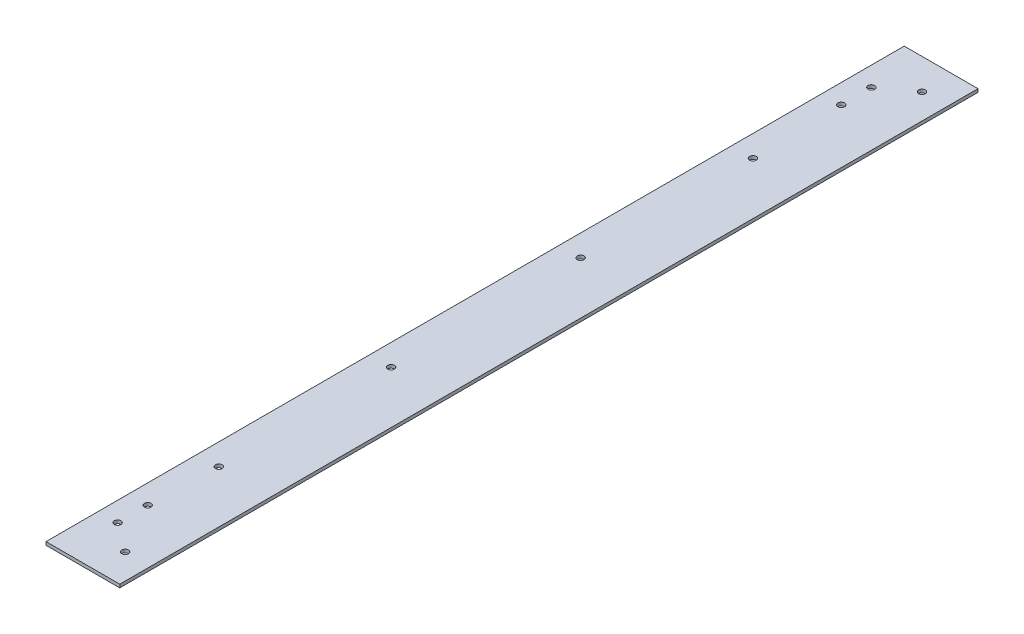
SolidWorks part; units mm, degrees
ref_plane "Alzado" through (0, 0, 0) normal (0, 0, 1) x (1, 0, 0)
ref_plane "Planta" through (0, 0, 0) normal (0, 1, 0) x (1, 0, 0)
ref_plane "Vista lateral" through (0, 0, 0) normal (1, 0, 0) x (0, 0, -1)
sketch "Croquis1" plane through (0, 0, 0) normal (0, 1, 0) x (1, 0, 0)
  line L1 (0, 0) -> (35, 0)
  line L2 (0, 0) -> (0, -400)
  line L3 (0, -400) -> (35, -400)
  line L4 (35, 0) -> (35, -400)
  dimension "D1" = 35
  dimension "D2" = 400
extrude "Saliente-Extruir1" add sketch "Croquis1" along normal blind 1.5
sketch "Croquis2" plane through (0, 1.5, 0) normal (0, 1, 0) x (1, 0, 0)
  line L0 (35, 0) -> (0, 0) construction
  line L1 (35, -400) -> (35, 0) construction
  line L2 (0, -400) -> (35, -400) construction
  circle A0 centre (22.5, -15) radius 1.55
  circle A1 centre (22.5, -385) radius 1.55
  dimension "D1" = 3.1
  dimension "D2" = 15
  dimension "D4" = 3.1
  dimension "D3" = 12.5
  dimension "D5" = 15
  dimension "D6" = 12.5
extrude "Cortar-Extruir1" cut sketch "Croquis2" against normal up to surface (1.5 mm away) up to face at (17.5, 0, 200)
sketch "Croquis3" plane through (0, 1.5, 0) normal (0, 1, 0) x (1, 0, 0)
  line L0 (0, 0) -> (0, -400) construction
  line L1 (35, 0) -> (0, 0) construction
  line L2 (0, -400) -> (35, -400) construction
  line L3 (0, 0) -> (0, -400) construction
  line L4 (35, -200) -> (0, -200) construction
  line L5 (35, -400) -> (35, 0) construction
  line L6 (35, 0) -> (0, 0) construction
  circle A0 centre (9, -25) radius 1.55
  circle A1 centre (9, -39) radius 1.55
  circle A2 centre (9, -375) radius 1.55
  circle A3 centre (9, -361) radius 1.55
  dimension "D1" = 3.1
  dimension "D5" = 3.1
  dimension "D2" = 14
  dimension "D3" = 9
  dimension "D4" = 25
  dimension "D6" = 14
  dimension "D7" = 25
  dimension "D8" = 9
  dimension "D9" = 200
extrude "Cortar-Extruir2" cut sketch "Croquis3" against normal up to surface (1.5 mm away) up to face at (22.5, 0, 16.55)
sketch "Croquis5" plane through (0, 1.5, 0) normal (0, 1, 0) x (1, 0, 0)
  line L0 (0, -400) -> (35, -400) construction
  line L1 (35, -400) -> (35, 0) construction
  line L2 (35, 0) -> (0, 0) construction
  circle A0 centre (10, -81) radius 1.55
  circle A1 centre (10, -161) radius 1.55
  circle A2 centre (10, -249) radius 1.55
  circle A3 centre (10, -329) radius 1.55
  dimension "D1" = 3.1
  dimension "D7" = 71
  dimension "D2" = 80
  dimension "D3" = 80
  dimension "D4" = 25
  dimension "D5" = 25
  dimension "D6" = 81
extrude "Cortar-Extruir3" cut sketch "Croquis5" against normal up to surface (1.5 mm away) up to face at (9, 0, 26.55)
sketch "Croquis6" plane through (0, 1.5, 0) normal (0, 1, 0) x (1, 0, 0)
  line L8 (0.75, -0.75) -> (0.75, -399.25)
  line L9 (0.75, -399.25) -> (34.25, -399.25)
  line L10 (34.25, -399.25) -> (34.25, -0.75)
  line L11 (34.25, -0.75) -> (0.75, -0.75)
  line L12 (0.75, -0.75) -> (0.75, -399.25)
  line L13 (0.75, -399.25) -> (34.25, -399.25)
  line L14 (34.25, -399.25) -> (34.25, -0.75)
  line L15 (34.25, -0.75) -> (0.75, -0.75)
  dimension "D1" = 0.75
extrude "Cortar-Extruir4" cut sketch "Croquis6" against normal up to surface (1.5 mm away) flip side to cut up to face at (10, 0, 82.55)
sketch "Croquis7" plane through (0, 1.5, 0) normal (0, 1, 0) x (1, 0, 0)
  line L1 (0.75, -0.75) -> (0, -0.75)
  line L2 (0.75, -0.75) -> (0.75, -399.25)
  line L3 (0.75, -399.25) -> (0, -399.25)
  line L4 (0, -0.75) -> (0, -399.25)
  point P5 (0.75, -399.25)
  dimension "D1" = 0.75
extrude "Saliente-Extruir2" add sketch "Croquis7" against normal up to surface (1.5 mm away) up to face at (22.5, 0, 386.55)
